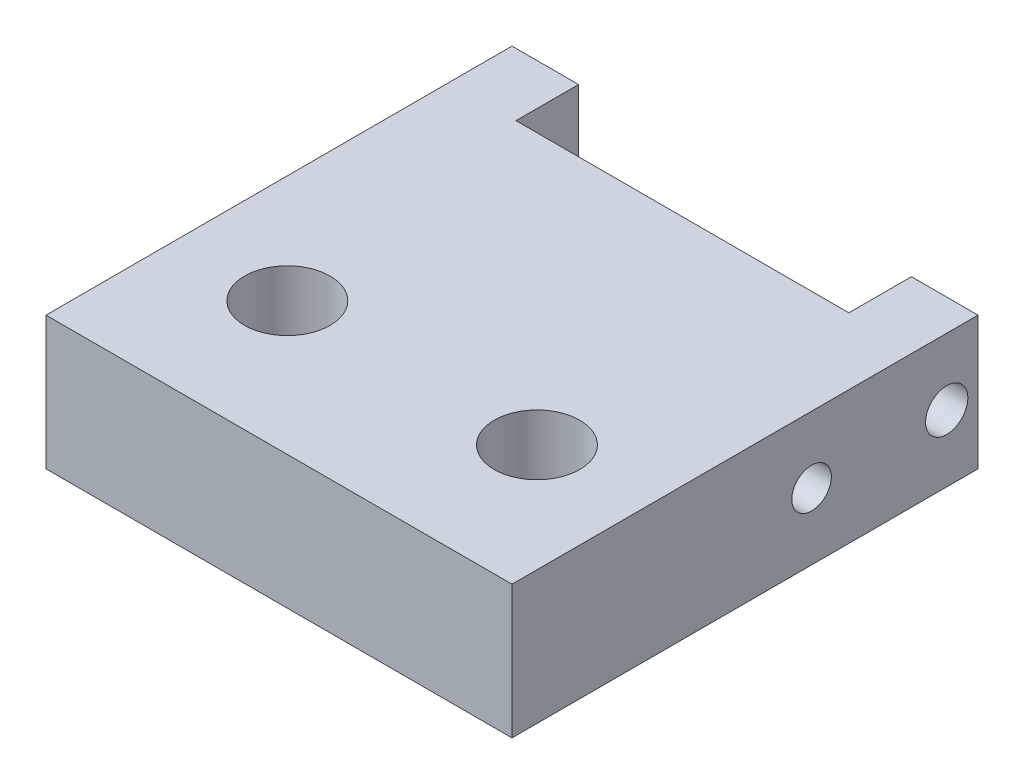
SolidWorks part; units mm, degrees
material "6061 Alloy"
ref_plane "Front Plane" through (0, 0, 0) normal (0, 0, 1) x (1, 0, 0)
ref_plane "Top Plane" through (0, 0, 0) normal (0, 1, 0) x (1, 0, 0)
ref_plane "Right Plane" through (0, 0, 0) normal (1, 0, 0) x (0, 0, -1)
sketch "Sketch1" plane through (0, 0, 0) normal (0, 1, 0) x (1, 0, 0)
  line L1 (-8.89, -8.89) -> (8.89, -8.89)
  line L2 (-8.89, -8.89) -> (-8.89, 8.89)
  line L3 (-8.89, 8.89) -> (8.89, 8.89)
  line L4 (8.89, -8.89) -> (8.89, 8.89)
  line L5 (-8.89, -8.89) -> (8.89, 8.89) construction
  line L6 (-8.89, 8.89) -> (8.89, -8.89) construction
  point P0 (0, 0)
  dimension "D1" = 17.78
  dimension "D2" = 17.78
extrude "Boss-Extrude1" add sketch "Sketch1" along normal blind 5.08
sketch "Sketch2" plane through (0, 5.08, 0) normal (0, 1, 0) x (1, 0, 0)
  line L0 (8.89, 8.89) -> (-8.89, 8.89) construction
  line L1 (-6.35, 11.2776) -> (6.35, 11.2776)
  line L2 (-6.35, 11.2776) -> (-6.35, 6.5024)
  line L3 (-6.35, 6.5024) -> (6.35, 6.5024)
  line L4 (6.35, 11.2776) -> (6.35, 6.5024)
  line L5 (-6.35, 11.2776) -> (6.35, 6.5024) construction
  line L6 (-6.35, 6.5024) -> (6.35, 11.2776) construction
  line L7 (-8.89, 8.89) -> (-8.89, -8.89) construction
  point P0 (0, 8.89)
  dimension "D1" = 2.3876
  dimension "D2" = 2.54
extrude "Cut-Extrude1" cut sketch "Sketch2" against normal through all contours L1 L4 L3 L2
hole_wizard "#4 Clearance Hole1" positions "Sketch6" profile "Sketch7" hole size "#4" standard "ANSI Inch" end condition through all
sketch "Sketch6" plane through (0, 5.08, 0) normal (0, 1, 0) x (1, 0, 0)
  line L0 (8.89, 8.89) -> (6.35, 8.89) construction
  line L2 (8.89, -8.89) -> (8.89, 8.89) construction
  line L4 (-6.35, 8.89) -> (-8.89, 8.89) construction
  point P0 (4.7625, -3.81)
  point P9 (-4.7625, -3.81)
  dimension "D1" = 12.7
  dimension "D2" = 4.1275
  dimension "D3" = 12.7
  dimension "D4" = 9.525
sketch "Sketch7" plane through (4.7625, 5.08, 3.81) normal (1, 0, 0) x (0, 0, 1)
  line L0 (0, 0) -> (0, 5.08)
  line L1 (0, 5.08) -> (1.6319, 5.08)
  line L2 (1.6319, 5.08) -> (1.6319, 0)
  line L5 (1.6319, 0) -> (0, 0)
  line L11 (0, -6.35) -> (0, 107.95) construction
  dimension "Thru Hole Dia." = 3.2639
  dimension "Thru Hole Depth" = 5.08
hole_wizard "#0 Clearance Hole1" positions "Sketch10" profile "Sketch11" hole size "#0" standard "ANSI Inch" end condition through all
sketch "Sketch10" plane through (8.89, 0, 0) normal (1, 0, 0) x (0, 0, -1)
  line L0 (-8.89, 5.08) -> (8.89, 5.08) construction
  line L1 (8.89, 5.08) -> (8.89, 0) construction
  point P0 (7.6962, 2.54)
  dimension "D1" = 2.54
  dimension "D2" = 1.1938
sketch "Sketch11" plane through (8.89, 2.54, -7.6962) normal (0, 1, 0) x (0, 0, -1)
  line L0 (0, 0) -> (0, 17.78)
  line L1 (0, 17.78) -> (0.8064, 17.78)
  line L2 (0.8064, 17.78) -> (0.8064, 0)
  line L5 (0.8064, 0) -> (0, 0)
  line L11 (0, -6.35) -> (0, 107.95) construction
  dimension "Thru Hole Dia." = 1.6129
  dimension "Thru Hole Depth" = 17.78
hole_wizard "#1-72 Tapped Hole1" positions "Sketch14" profile "Sketch15" tap size "#1-72" standard "ANSI Inch" end condition through all
sketch "Sketch14" plane through (8.89, 0, 0) normal (1, 0, 0) x (0, 0, -1)
  line L1 (-8.89, 5.08) -> (8.89, 5.08) construction
  line L2 (8.89, 5.08) -> (8.89, 0) construction
  point P0 (2.54, 2.54)
  dimension "D1" = 2.54
  dimension "D2" = 6.35
cosmetic thread "Hole Thread1" parameters "D2"=1.8542
sketch "Sketch15" plane through (8.89, 2.54, -2.54) normal (0, 1, 0) x (0, 0, -1)
  line L0 (0, 0) -> (0, 17.78)
  line L1 (0, 17.78) -> (0.7556, 17.78)
  line L2 (0.7556, 17.78) -> (0.7556, 0)
  line L5 (0.7556, 0) -> (0, 0)
  line L11 (0, -6.35) -> (0, 107.95) construction
  dimension "Thru Tap Drill Dia." = 1.5113
  dimension "Thru Tap Drill Depth" = 17.78
